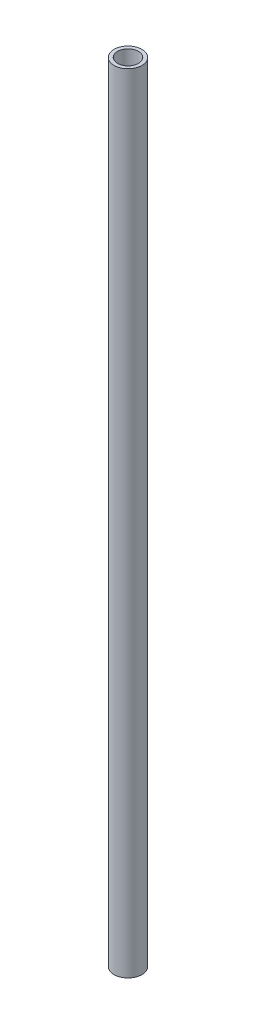
SolidWorks part; units mm, degrees
material "Hexcel AS4C (3000 丝)"
ref_plane "前视基准面" through (0, 0, 0) normal (0, 0, 1) x (1, 0, 0)
ref_plane "上视基准面" through (0, 0, 0) normal (0, 1, 0) x (1, 0, 0)
ref_plane "右视基准面" through (0, 0, 0) normal (1, 0, 0) x (0, 0, -1)
sketch "草图1" plane through (0, 0, 0) normal (0, 1, 0) x (1, 0, 0)
  circle A0 centre (0, 0) radius 4
  circle A1 centre (0, 0) radius 3
  dimension "D1" = 8
  dimension "D2" = 6
extrude "凸台-拉伸1" add sketch "草图1" along normal blind 226
